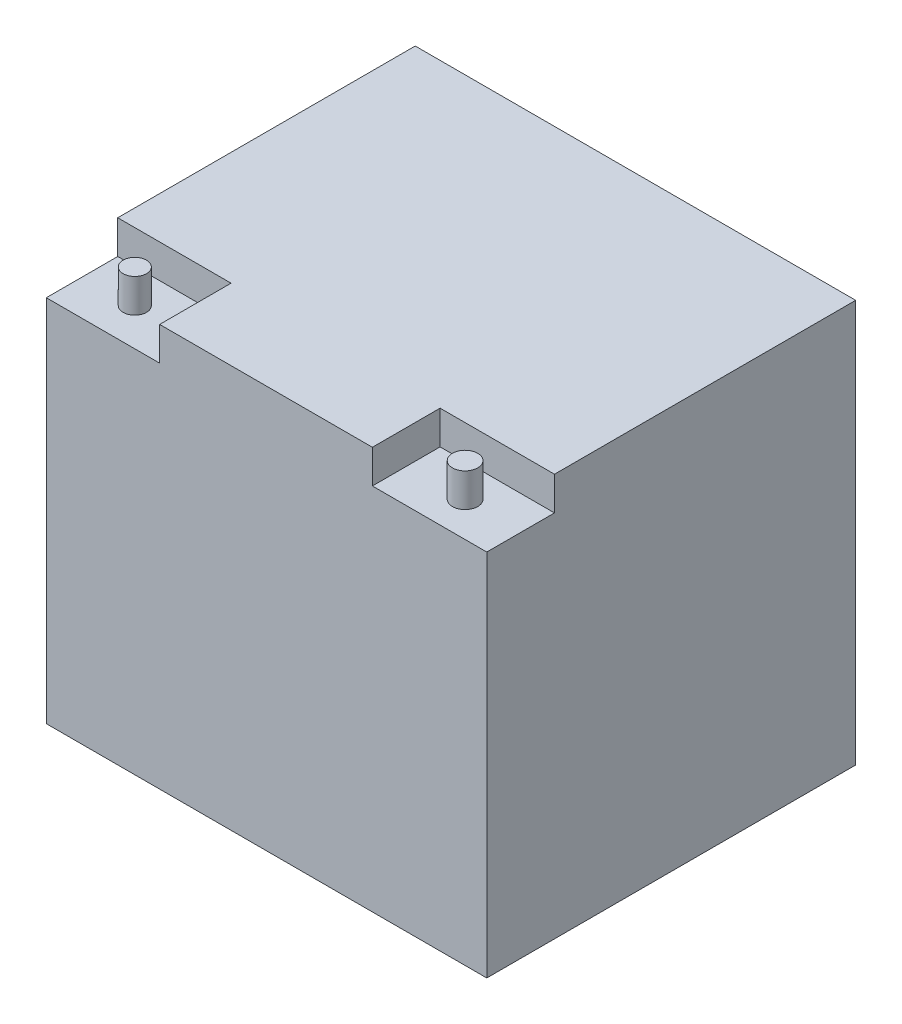
SolidWorks part; units mm, degrees
ref_plane "前视基准面" through (0, 0, 0) normal (0, 0, 1) x (1, 0, 0)
ref_plane "上视基准面" through (0, 0, 0) normal (0, 1, 0) x (1, 0, 0)
ref_plane "右视基准面" through (0, 0, 0) normal (1, 0, 0) x (0, 0, -1)
sketch "草图2" plane through (0, 0, 0) normal (0, 1, 0) x (1, 0, 0)
  line L1 (-98.5, 82.5) -> (98.5, 82.5)
  line L2 (-98.5, 82.5) -> (-98.5, -82.5)
  line L3 (-98.5, -82.5) -> (98.5, -82.5)
  line L4 (98.5, 82.5) -> (98.5, -82.5)
  line L5 (-98.5, 82.5) -> (98.5, -82.5) construction
  line L6 (-98.5, -82.5) -> (98.5, 82.5) construction
  point P0 (0, 0)
  dimension "D1" = 197
  dimension "D2" = 165
extrude "凸台-拉伸1" add sketch "草图2" along normal blind 180
sketch "草图3" plane through (0, 180, 0) normal (0, 1, 0) x (1, 0, 0)
  line L1 (-98.5, -82.5) -> (-47.815, -82.5)
  line L2 (-98.5, -82.5) -> (-98.5, -50.5507)
  line L3 (-98.5, -50.5507) -> (-47.815, -50.5507)
  line L4 (-47.815, -82.5) -> (-47.815, -50.5507)
extrude "切除-拉伸2" cut sketch "草图3" against normal blind 15
sketch "草图4" plane through (0, 180, 0) normal (0, 1, 0) x (1, 0, 0)
  line L1 (98.5, -82.5) -> (47.3392, -82.5)
  line L2 (98.5, -82.5) -> (98.5, -52.2159)
  line L3 (98.5, -52.2159) -> (47.3392, -52.2159)
  line L4 (47.3392, -82.5) -> (47.3392, -52.2159)
extrude "切除-拉伸3" cut sketch "草图4" against normal blind 15
sketch "草图5" plane through (0, 165, 0) normal (0, 1, 0) x (1, 0, 0)
  circle A0 centre (-75.6476, -65.7754) radius 5.2389
extrude "凸台-拉伸2" add sketch "草图5" along normal blind 15
sketch "草图6" plane through (0, 165, 0) normal (0, 1, 0) x (1, 0, 0)
  circle A0 centre (73.2281, -66.9271) radius 5.6535
extrude "凸台-拉伸3" add sketch "草图6" along normal blind 15
